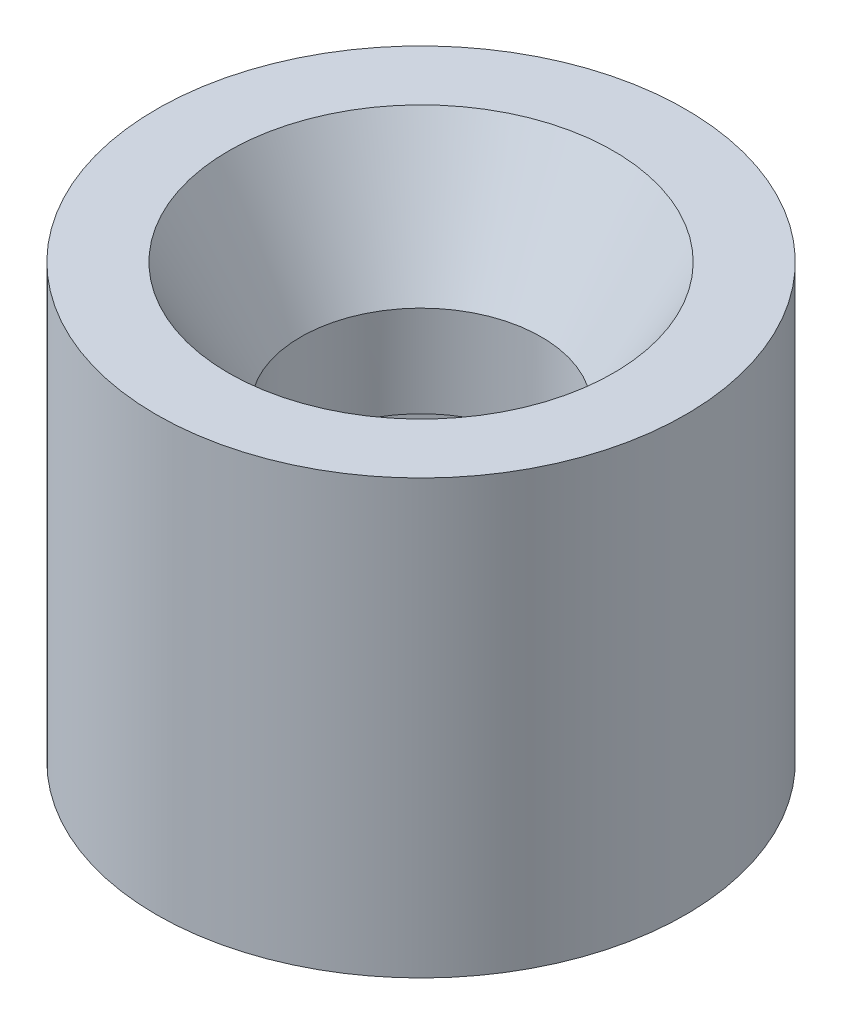
SolidWorks part; units mm, degrees
material "PVC 0.007 Plasticized"
ref_plane "Front Plane" through (0, 0, 0) normal (0, 0, 1) x (1, 0, 0)
ref_plane "Top Plane" through (0, 0, 0) normal (0, 1, 0) x (1, 0, 0)
ref_plane "Right Plane" through (0, 0, 0) normal (1, 0, 0) x (0, 0, -1)
other "Configuration Table"
sketch "Sketch1" plane through (0, 0, 0) normal (0, 1, 0) x (1, 0, 0)
  circle A0 centre (0, 0) radius 6.985
  dimension "D1" = 13.97
extrude "Boss-Extrude1" add sketch "Sketch1" along normal blind 11.43
hole_wizard "CSK for 1/4 Flat Head Machine Screw (100)1" positions "Sketch2" profile "Sketch3" countersink size "1/4" standard "ANSI Inch" end condition through all
sketch "Sketch2" plane through (0, 11.43, 0) normal (0, 1, 0) x (1, 0, 0)
  point P0 (0, 0)
sketch "Sketch3" plane through (0, 11.43, 0) normal (1, 0, 0) x (0, 0, 1)
  line L0 (0, 0) -> (0, 11.43)
  line L1 (0, 11.43) -> (3.175, 11.43)
  line L2 (3.175, 11.43) -> (3.175, 3.2996)
  line L3 (3.175, 3.2996) -> (5.08, 0)
  line L5 (5.08, 0) -> (0, 0)
  line L6 (-3.175, 3.2996) -> (-5.08, 0) construction
  line L11 (0, -6.35) -> (0, 107.95) construction
  dimension "Thru Hole Dia." = 6.35
  dimension "Thru Hole Depth" = 11.43
  dimension "Near C'Sink Dia." = 10.16
  dimension "Near C'Sink Angle" = 60
sketch "Sketch4" plane through (0, 0, 0) normal (0, -1, 0) x (1, 0, 0)
  line L1 (5.4379, -3.7386) -> (5.9567, 2.8401)
  line L2 (5.9567, 2.8401) -> (0.5187, 6.5787)
  line L3 (0.5187, 6.5787) -> (-5.4379, 3.7386)
  line L4 (-5.4379, 3.7386) -> (-5.9567, -2.8401)
  line L5 (-5.9567, -2.8401) -> (-0.5187, -6.5787)
  line L6 (-0.5187, -6.5787) -> (5.4379, -3.7386)
  circle A0 centre (0, 0) radius 5.715 construction
  dimension "D1" = 11.43
extrude "Cut-Extrude1" cut sketch "Sketch4" against normal blind 5.715
